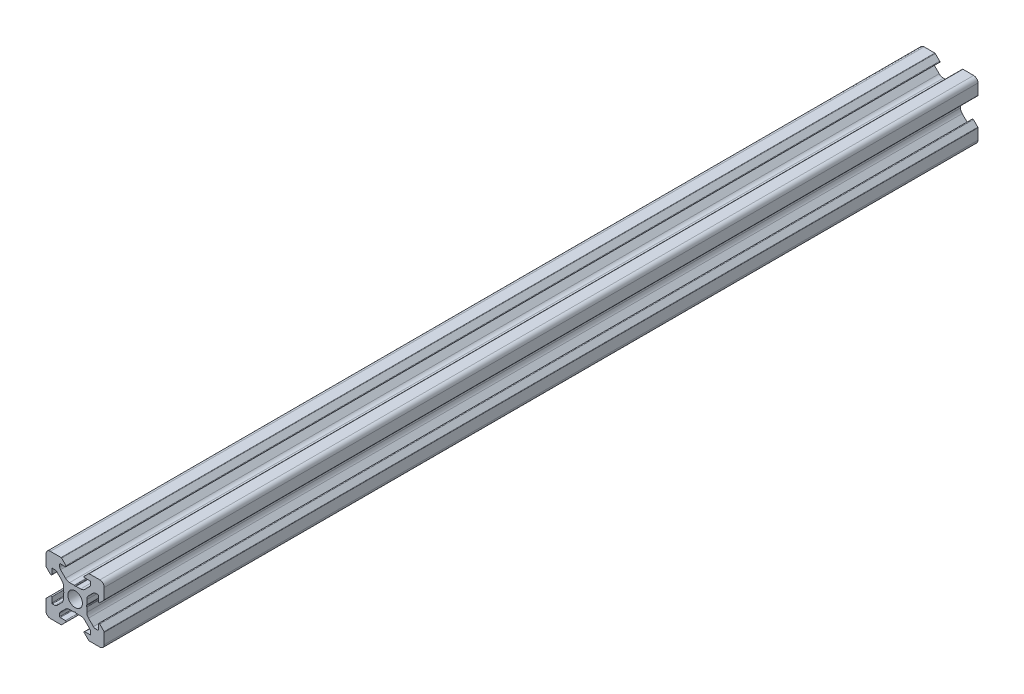
SolidWorks part; units mm, degrees
ref_plane "Спереди" through (0, 0, 0) normal (0, 0, 1) x (1, 0, 0)
ref_plane "Сверху" through (0, 0, 0) normal (0, 1, 0) x (1, 0, 0)
ref_plane "Справа" through (0, 0, 0) normal (1, 0, 0) x (0, 0, -1)
sketch "Model" plane through (0, 0, 0) normal (0, 0, 1) x (1, 0, 0)
  line L0 (18.9421, 33.3622) -> (18.9421, 34.9233)
  line L1 (18.3564, 36.3375) -> (16.6623, 38.0316)
  line L2 (15.9551, 38.3245) -> (15.1421, 38.3245)
  line L3 (14.9421, 38.1245) -> (14.9421, 36.3545)
  line L4 (13.0154, 37.6777) -> (14.5154, 36.1777)
  line L5 (12.9421, 37.8545) -> (12.9421, 41.5245)
  line L6 (18.2889, 42.9513) -> (19.7889, 41.4513)
  line L7 (22.7606, 36.9697) -> (22.9421, 36.8245)
  line L8 (23.1237, 36.9697) -> (22.9421, 36.8245)
  line L9 (23.2798, 37.0245) -> (24.8409, 37.0245)
  line L10 (26.2551, 37.6103) -> (27.9493, 39.3044)
  line L11 (28.2421, 40.0115) -> (28.2421, 40.8245)
  line L12 (28.0421, 41.0245) -> (26.2721, 41.0245)
  line L13 (27.5954, 42.9513) -> (26.0954, 41.4513)
  line L14 (27.7721, 43.0245) -> (31.4421, 43.0245)
  line L15 (32.9421, 37.8545) -> (32.9421, 41.5245)
  line L16 (32.8689, 37.6777) -> (31.3689, 36.1777)
  line L17 (30.9421, 38.1245) -> (30.9421, 36.3545)
  line L18 (29.9292, 38.3245) -> (30.7421, 38.3245)
  line L19 (27.5279, 36.3375) -> (29.222, 38.0316)
  line L20 (26.9421, 33.3622) -> (26.9421, 34.9233)
  line L21 (26.8874, 33.206) -> (26.7421, 33.0245)
  line L22 (26.8874, 32.843) -> (26.7421, 33.0245)
  line L23 (26.9421, 32.6868) -> (26.9421, 31.1257)
  line L24 (27.5279, 29.7115) -> (29.222, 28.0174)
  line L25 (29.9292, 27.7245) -> (30.7421, 27.7245)
  line L26 (30.9421, 27.9245) -> (30.9421, 29.6945)
  line L27 (32.8689, 28.3713) -> (31.3689, 29.8713)
  line L28 (32.9421, 28.1945) -> (32.9421, 24.5245)
  line L29 (27.7721, 23.0245) -> (31.4421, 23.0245)
  line L30 (27.5954, 23.0977) -> (26.0954, 24.5977)
  line L31 (28.0421, 25.0245) -> (26.2721, 25.0245)
  line L32 (28.2421, 26.0375) -> (28.2421, 25.2245)
  line L33 (26.2551, 28.4387) -> (27.9493, 26.7446)
  line L34 (23.2798, 29.0245) -> (24.8409, 29.0245)
  line L35 (23.1237, 29.0793) -> (22.9421, 29.2245)
  line L36 (22.7606, 29.0793) -> (22.9421, 29.2245)
  line L37 (19.6292, 28.4387) -> (17.935, 26.7446)
  line L38 (17.6421, 26.0375) -> (17.6421, 25.2245)
  line L39 (17.8421, 25.0245) -> (19.6121, 25.0245)
  line L40 (18.2889, 23.0977) -> (19.7889, 24.5977)
  line L41 (18.1121, 23.0245) -> (14.4421, 23.0245)
  line L42 (12.9421, 28.1945) -> (12.9421, 24.5245)
  line L43 (13.0154, 28.3713) -> (14.5154, 29.8713)
  line L44 (14.9421, 27.9245) -> (14.9421, 29.6945)
  line L45 (15.9551, 27.7245) -> (15.1421, 27.7245)
  line L46 (18.3564, 29.7115) -> (16.6623, 28.0174)
  line L47 (18.9421, 32.6868) -> (18.9421, 31.1257)
  line L48 (18.9969, 32.843) -> (19.1421, 33.0245)
  line L49 (18.9969, 33.206) -> (19.1421, 33.0245)
  line L50 (22.6045, 29.0245) -> (21.0434, 29.0245)
  line L51 (22.6045, 37.0245) -> (21.0434, 37.0245)
  line L52 (19.6292, 37.6103) -> (17.935, 39.3044)
  line L53 (17.6421, 40.0115) -> (17.6421, 40.8245)
  line L54 (17.8421, 41.0245) -> (19.6121, 41.0245)
  line L55 (18.1121, 43.0245) -> (14.4421, 43.0245)
  arc A0 (18.9421, 33.3622) -> (18.9969, 33.206) centre (19.1921, 33.3622) ccw
  arc A1 (18.9421, 34.9233) -> (18.3564, 36.3375) centre (16.9421, 34.9233) ccw
  arc A2 (16.6623, 38.0316) -> (15.9551, 38.3245) centre (15.9551, 37.3245) ccw
  arc A3 (15.1421, 38.3245) -> (14.9421, 38.1245) centre (15.1421, 38.1245) ccw
  arc A4 (14.5154, 36.1777) -> (14.9421, 36.3545) centre (14.6921, 36.3545) ccw
  arc A5 (12.9421, 37.8545) -> (13.0154, 37.6777) centre (13.1921, 37.8545) ccw
  arc A6 (14.4421, 43.0245) -> (12.9421, 41.5245) centre (14.4421, 41.5245) ccw
  arc A7 (18.2889, 42.9513) -> (18.1121, 43.0245) centre (18.1121, 42.7745) ccw
  arc A8 (19.6121, 41.0245) -> (19.7889, 41.4513) centre (19.6121, 41.2745) ccw
  arc A9 (17.8421, 41.0245) -> (17.6421, 40.8245) centre (17.8421, 40.8245) ccw
  arc A10 (17.6421, 40.0115) -> (17.935, 39.3044) centre (18.6421, 40.0115) ccw
  arc A11 (19.6292, 37.6103) -> (21.0434, 37.0245) centre (21.0434, 39.0245) ccw
  arc A12 (22.7606, 36.9697) -> (22.6045, 37.0245) centre (22.6045, 36.7745) ccw
  arc A13 (23.2798, 37.0245) -> (23.1237, 36.9697) centre (23.2798, 36.7745) ccw
  arc A14 (24.8409, 37.0245) -> (26.2551, 37.6103) centre (24.8409, 39.0245) ccw
  arc A15 (27.9493, 39.3044) -> (28.2421, 40.0115) centre (27.2421, 40.0115) ccw
  arc A16 (28.2421, 40.8245) -> (28.0421, 41.0245) centre (28.0421, 40.8245) ccw
  arc A17 (26.0954, 41.4513) -> (26.2721, 41.0245) centre (26.2721, 41.2745) ccw
  arc A18 (27.7721, 43.0245) -> (27.5954, 42.9513) centre (27.7721, 42.7745) ccw
  arc A19 (32.9421, 41.5245) -> (31.4421, 43.0245) centre (31.4421, 41.5245) ccw
  arc A20 (32.8689, 37.6777) -> (32.9421, 37.8545) centre (32.6921, 37.8545) ccw
  arc A21 (30.9421, 36.3545) -> (31.3689, 36.1777) centre (31.1921, 36.3545) ccw
  arc A22 (30.9421, 38.1245) -> (30.7421, 38.3245) centre (30.7421, 38.1245) ccw
  arc A23 (29.9292, 38.3245) -> (29.222, 38.0316) centre (29.9292, 37.3245) ccw
  arc A24 (27.5279, 36.3375) -> (26.9421, 34.9233) centre (28.9421, 34.9233) ccw
  arc A25 (26.8874, 33.206) -> (26.9421, 33.3622) centre (26.6921, 33.3622) ccw
  arc A26 (26.9421, 32.6868) -> (26.8874, 32.843) centre (26.6921, 32.6868) ccw
  arc A27 (26.9421, 31.1257) -> (27.5279, 29.7115) centre (28.9421, 31.1257) ccw
  arc A28 (29.222, 28.0174) -> (29.9292, 27.7245) centre (29.9292, 28.7245) ccw
  arc A29 (30.7421, 27.7245) -> (30.9421, 27.9245) centre (30.7421, 27.9245) ccw
  arc A30 (31.3689, 29.8713) -> (30.9421, 29.6945) centre (31.1921, 29.6945) ccw
  arc A31 (32.9421, 28.1945) -> (32.8689, 28.3713) centre (32.6921, 28.1945) ccw
  arc A32 (31.4421, 23.0245) -> (32.9421, 24.5245) centre (31.4421, 24.5245) ccw
  arc A33 (27.5954, 23.0977) -> (27.7721, 23.0245) centre (27.7721, 23.2745) ccw
  arc A34 (26.2721, 25.0245) -> (26.0954, 24.5977) centre (26.2721, 24.7745) ccw
  arc A35 (28.0421, 25.0245) -> (28.2421, 25.2245) centre (28.0421, 25.2245) ccw
  arc A36 (28.2421, 26.0375) -> (27.9493, 26.7446) centre (27.2421, 26.0375) ccw
  arc A37 (26.2551, 28.4387) -> (24.8409, 29.0245) centre (24.8409, 27.0245) ccw
  arc A38 (23.1237, 29.0793) -> (23.2798, 29.0245) centre (23.2798, 29.2745) ccw
  arc A39 (22.6045, 29.0245) -> (22.7606, 29.0793) centre (22.6045, 29.2745) ccw
  arc A40 (21.0434, 29.0245) -> (19.6292, 28.4387) centre (21.0434, 27.0245) ccw
  arc A41 (17.935, 26.7446) -> (17.6421, 26.0375) centre (18.6421, 26.0375) ccw
  arc A42 (17.6421, 25.2245) -> (17.8421, 25.0245) centre (17.8421, 25.2245) ccw
  arc A43 (19.7889, 24.5977) -> (19.6121, 25.0245) centre (19.6121, 24.7745) ccw
  arc A44 (18.1121, 23.0245) -> (18.2889, 23.0977) centre (18.1121, 23.2745) ccw
  arc A45 (12.9421, 24.5245) -> (14.4421, 23.0245) centre (14.4421, 24.5245) ccw
  arc A46 (13.0154, 28.3713) -> (12.9421, 28.1945) centre (13.1921, 28.1945) ccw
  arc A47 (14.9421, 29.6945) -> (14.5154, 29.8713) centre (14.6921, 29.6945) ccw
  arc A48 (14.9421, 27.9245) -> (15.1421, 27.7245) centre (15.1421, 27.9245) ccw
  arc A49 (15.9551, 27.7245) -> (16.6623, 28.0174) centre (15.9551, 28.7245) ccw
  arc A50 (18.3564, 29.7115) -> (18.9421, 31.1257) centre (16.9421, 31.1257) ccw
  arc A51 (18.9969, 32.843) -> (18.9421, 32.6868) centre (19.1921, 32.6868) ccw
  circle A52 centre (22.9421, 33.0245) radius 2.5
extrude "Бобышка-Вытянуть1" add sketch "Model" along normal blind 300
